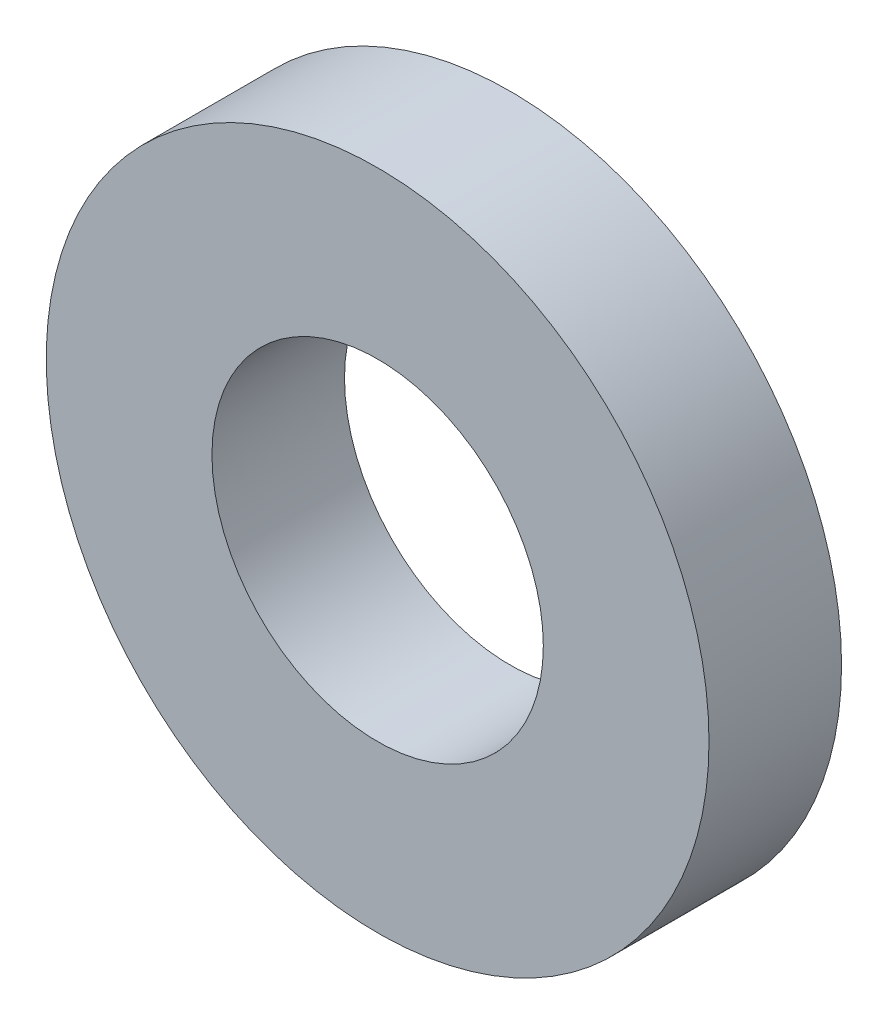
SolidWorks part; units mm, degrees
ref_plane "Front Plane" through (0, 0, 0) normal (0, 0, 1) x (1, 0, 0)
ref_plane "Top Plane" through (0, 0, 0) normal (0, 1, 0) x (1, 0, 0)
ref_plane "Right Plane" through (0, 0, 0) normal (1, 0, 0) x (0, 0, -1)
sketch "Sketch1" plane through (0, 0, 0) normal (0, 0, 1) x (1, 0, 0)
  circle A0 centre (0, 0) radius 2.5
  circle A1 centre (0, 0) radius 1.25
  dimension "D1" = 5
  dimension "D2" = 2.5
extrude "Boss-Extrude1" add sketch "Sketch1" along normal mid plane 1
